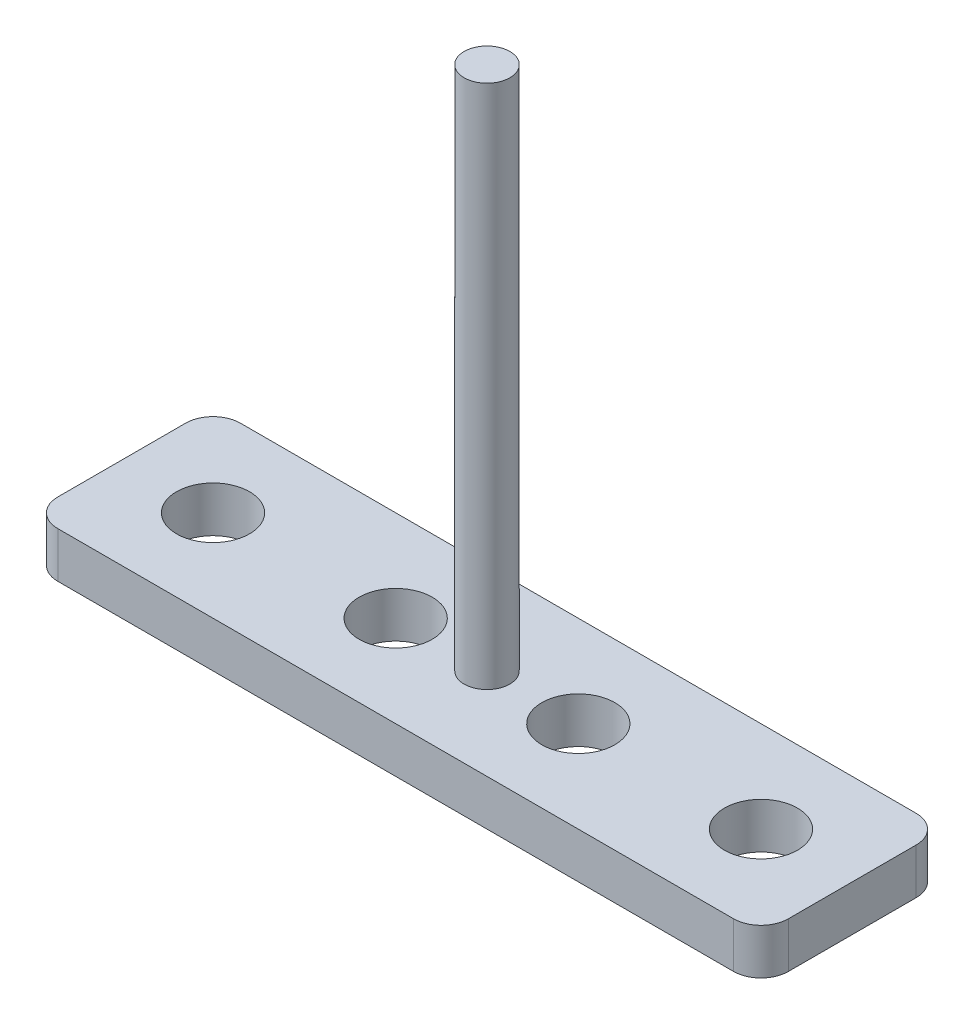
SolidWorks part; units mm, degrees
ref_plane "Front Plane" through (0, 0, 0) normal (0, 0, 1) x (1, 0, 0)
ref_plane "Top Plane" through (0, 0, 0) normal (0, 1, 0) x (1, 0, 0)
ref_plane "Right Plane" through (0, 0, 0) normal (1, 0, 0) x (0, 0, -1)
sketch "Sketch1" plane through (0, 0, 0) normal (0, 1, 0) x (1, 0, 0)
  line L1 (-40, -10) -> (40, -10)
  line L2 (-40, -10) -> (-40, 10)
  line L3 (-40, 10) -> (40, 10)
  line L4 (40, -10) -> (40, 10)
  line L5 (-40, -10) -> (40, 10) construction
  line L6 (-40, 10) -> (40, -10) construction
  point P0 (0, 0)
  point P9 (0, 0)
  dimension "D1" = 80
  dimension "D2" = 20
sketch "Sketch2" plane through (0, 0, 0) normal (0, 1, 0) x (1, 0, 0)
  line L0 (-10, 0) -> (10, 0) construction
  line L1 (-30, 0) -> (30, 0) construction
  point P4 (0, 0)
  point P8 (0, 0)
  dimension "D1" = 20
  dimension "D2" = 60
extrude "Boss-Extrude1" add sketch "Sketch1" along normal mid plane 5
hole_wizard "Ø8.0mm Dowel Hole1" positions "Sketch4" profile "Sketch5" hole size "Ø8.0" standard "ANSI Metric" end condition through all
sketch "Sketch4" plane through (0, 2.5, 0) normal (0, 1, 0) x (1, 0, 0)
  point P0 (-30, 0)
  point P3 (-10, 0)
  point P6 (10, 0)
  point P9 (30, 0)
sketch "Sketch5" plane through (-30, 2.5, 0) normal (1, 0, 0) x (0, 0, 1)
  line L0 (0, 0) -> (0, 5)
  line L1 (0, 5) -> (4, 5)
  line L2 (4, 5) -> (4, 0)
  line L5 (4, 0) -> (0, 0)
  line L11 (0, -6.35) -> (0, 107.95) construction
  dimension "Thru Hole Dia." = 8
  dimension "Thru Hole Depth" = 5
sketch "Sketch6" plane through (0, 0, 0) normal (0, 1, 0) x (1, 0, 0)
  circle A0 centre (0, 0) radius 2.5
  dimension "D1" = 5
extrude "Boss-Extrude2" add sketch "Sketch6" along normal blind 60
fillet "Fillet1" radius 3 4 edges at (40, 0, -10) (40, 0, 10) (-40, 0, 10) (-40, 0, -10)
